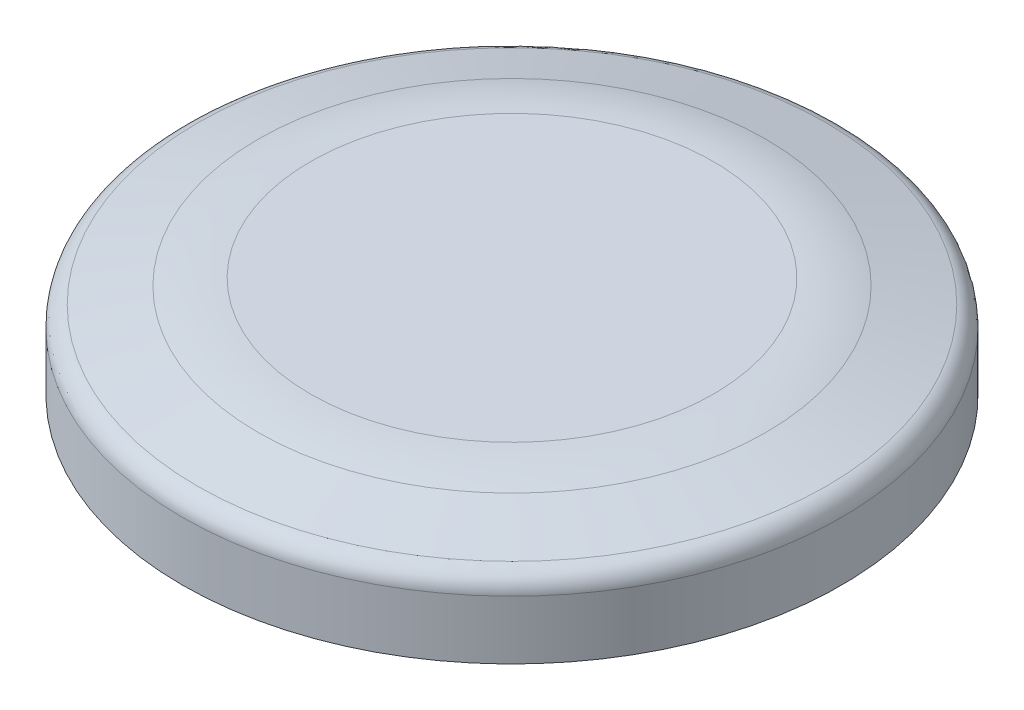
SolidWorks part; units mm, degrees
ref_plane "Front Plane" through (0, 0, 0) normal (0, 0, 1) x (1, 0, 0)
ref_plane "Top Plane" through (0, 0, 0) normal (0, 1, 0) x (1, 0, 0)
ref_plane "Right Plane" through (0, 0, 0) normal (1, 0, 0) x (0, 0, -1)
sketch "Sketch1" plane through (0, 0, 0) normal (0, 1, 0) x (1, 0, 0)
  circle A0 centre (0, 0) radius 3.25
  dimension "D1" = 6.5
extrude "Boss-Extrude1" add sketch "Sketch1" along normal blind 1
chamfer "Chamfer1" distance 1 angle 15 1 edges at (0, 1, 3.25)
fillet "Fillet1" radius 2 1 edges at (0, 1, 2.25)
fillet "Fillet2" radius 0.2 1 edges at (0, 0.7321, 3.25)
